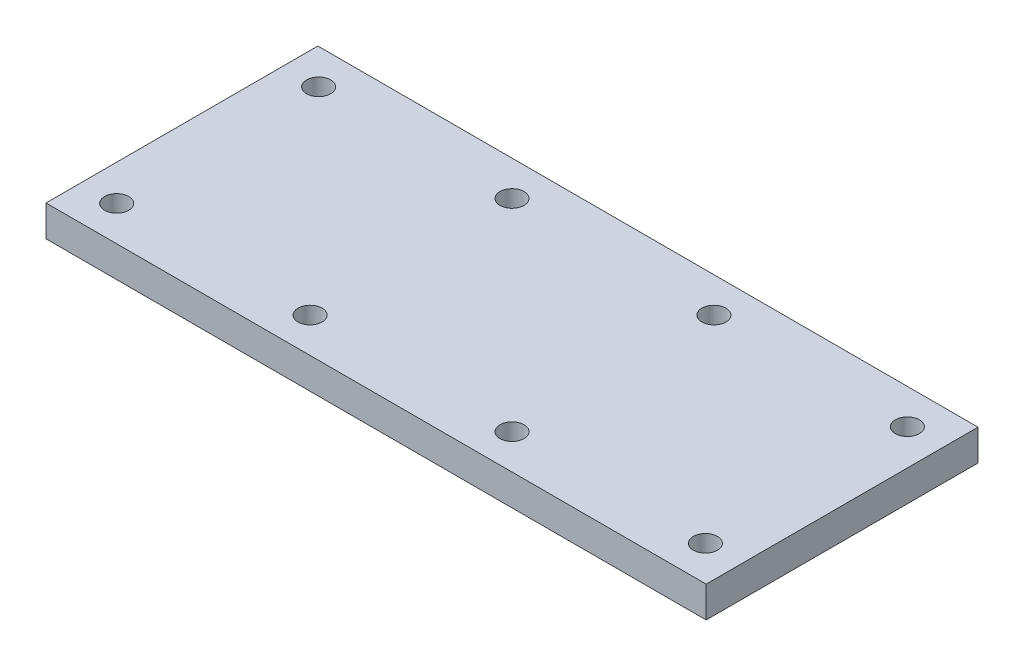
SolidWorks part; units mm, degrees
ref_plane "前视基准面" through (0, 0, 0) normal (0, 0, 1) x (1, 0, 0)
ref_plane "上视基准面" through (0, 0, 0) normal (0, 1, 0) x (1, 0, 0)
ref_plane "右视基准面" through (0, 0, 0) normal (1, 0, 0) x (0, 0, -1)
sketch "草图1" plane through (0, 0, 0) normal (0, 1, 0) x (1, 0, 0)
  line L0 (0, 17.5) -> (85, 17.5) construction
  line L1 (0, 0) -> (85, 0)
  line L2 (0, 0) -> (0, 35)
  line L3 (0, 35) -> (85, 35)
  line L4 (85, 0) -> (85, 35)
  line L5 (42.5, 35) -> (42.5, 0) construction
  circle A0 centre (80.4, 30.5) radius 1.55
  circle A1 centre (80.4, 4.5) radius 1.55
  circle A2 centre (4.6, 30.5) radius 1.55
  circle A3 centre (4.6, 4.5) radius 1.55
  circle A4 centre (55.5, 30.5) radius 1.55
  circle A5 centre (55.5, 4.5) radius 1.55
  circle A6 centre (29.5, 4.5) radius 1.55
  circle A7 centre (29.5, 30.5) radius 1.55
  point P11 (42.5, 17.5)
  dimension "D3" = 3.1
  dimension "D6" = 3.1
  dimension "D1" = 85
  dimension "D2" = 35
  dimension "D4" = 37.9
  dimension "D5" = 13
  dimension "D7" = 13
  dimension "D8" = 13
extrude "凸台-拉伸1" add sketch "草图1" along normal blind 4
ref_plane "基准面1" through (0, 4, 0) normal (0, 1, 0) x (1, 0, 0)
sketch "草图2" plane through (0, 4, 0) normal (0, 1, 0) x (1, 0, 0)
  line L0 (42.5, 35) -> (42.5, 0) construction
  line L1 (5.9568, 28.15) -> (7.3135, 30.5)
  line L2 (7.3135, 30.5) -> (5.9568, 32.85)
  line L3 (5.9568, 32.85) -> (3.2432, 32.85)
  line L4 (3.2432, 32.85) -> (1.8865, 30.5)
  line L5 (1.8865, 30.5) -> (3.2432, 28.15)
  line L6 (3.2432, 28.15) -> (5.9568, 28.15)
  line L7 (31.0877, 27.75) -> (32.6754, 30.5)
  line L8 (32.6754, 30.5) -> (31.0877, 33.25)
  line L9 (31.0877, 33.25) -> (27.9123, 33.25)
  line L10 (27.9123, 33.25) -> (26.3246, 30.5)
  line L11 (26.3246, 30.5) -> (27.9123, 27.75)
  line L12 (27.9123, 27.75) -> (31.0877, 27.75)
  line L13 (85, 35) -> (0, 35) construction
  line L14 (0, 0) -> (85, 0) construction
  line L15 (0, 17.5) -> (85, 17.5) construction
  line L16 (0, 35) -> (0, 0) construction
  line L17 (85, 0) -> (85, 35) construction
  line L18 (27.9123, 7.25) -> (31.0877, 7.25)
  line L19 (26.3246, 4.5) -> (27.9123, 7.25)
  line L20 (27.9123, 1.75) -> (26.3246, 4.5)
  line L21 (31.0877, 1.75) -> (27.9123, 1.75)
  line L22 (32.6754, 4.5) -> (31.0877, 1.75)
  line L23 (31.0877, 7.25) -> (32.6754, 4.5)
  line L24 (3.2432, 6.85) -> (5.9568, 6.85)
  line L25 (1.8865, 4.5) -> (3.2432, 6.85)
  line L26 (3.2432, 2.15) -> (1.8865, 4.5)
  line L27 (5.9568, 2.15) -> (3.2432, 2.15)
  line L28 (7.3135, 4.5) -> (5.9568, 2.15)
  line L29 (5.9568, 6.85) -> (7.3135, 4.5)
  line L30 (79.0432, 6.85) -> (77.6865, 4.5)
  line L31 (77.6865, 4.5) -> (79.0432, 2.15)
  line L32 (79.0432, 2.15) -> (81.7568, 2.15)
  line L33 (81.7568, 2.15) -> (83.1135, 4.5)
  line L34 (83.1135, 4.5) -> (81.7568, 6.85)
  line L35 (81.7568, 6.85) -> (79.0432, 6.85)
  line L36 (53.9123, 7.25) -> (52.3246, 4.5)
  line L37 (52.3246, 4.5) -> (53.9123, 1.75)
  line L38 (53.9123, 1.75) -> (57.0877, 1.75)
  line L39 (57.0877, 1.75) -> (58.6754, 4.5)
  line L40 (58.6754, 4.5) -> (57.0877, 7.25)
  line L41 (57.0877, 7.25) -> (53.9123, 7.25)
  line L42 (57.0877, 27.75) -> (53.9123, 27.75)
  line L43 (58.6754, 30.5) -> (57.0877, 27.75)
  line L44 (57.0877, 33.25) -> (58.6754, 30.5)
  line L45 (53.9123, 33.25) -> (57.0877, 33.25)
  line L46 (52.3246, 30.5) -> (53.9123, 33.25)
  line L47 (53.9123, 27.75) -> (52.3246, 30.5)
  line L48 (81.7568, 28.15) -> (79.0432, 28.15)
  line L49 (83.1135, 30.5) -> (81.7568, 28.15)
  line L50 (81.7568, 32.85) -> (83.1135, 30.5)
  line L51 (79.0432, 32.85) -> (81.7568, 32.85)
  line L52 (77.6865, 30.5) -> (79.0432, 32.85)
  line L53 (79.0432, 28.15) -> (77.6865, 30.5)
  circle A0 centre (4.6, 30.5) radius 2.35 construction
  circle A1 centre (29.5, 30.5) radius 2.75 construction
  dimension "D1" = 4.7
  dimension "D2" = 5.5
